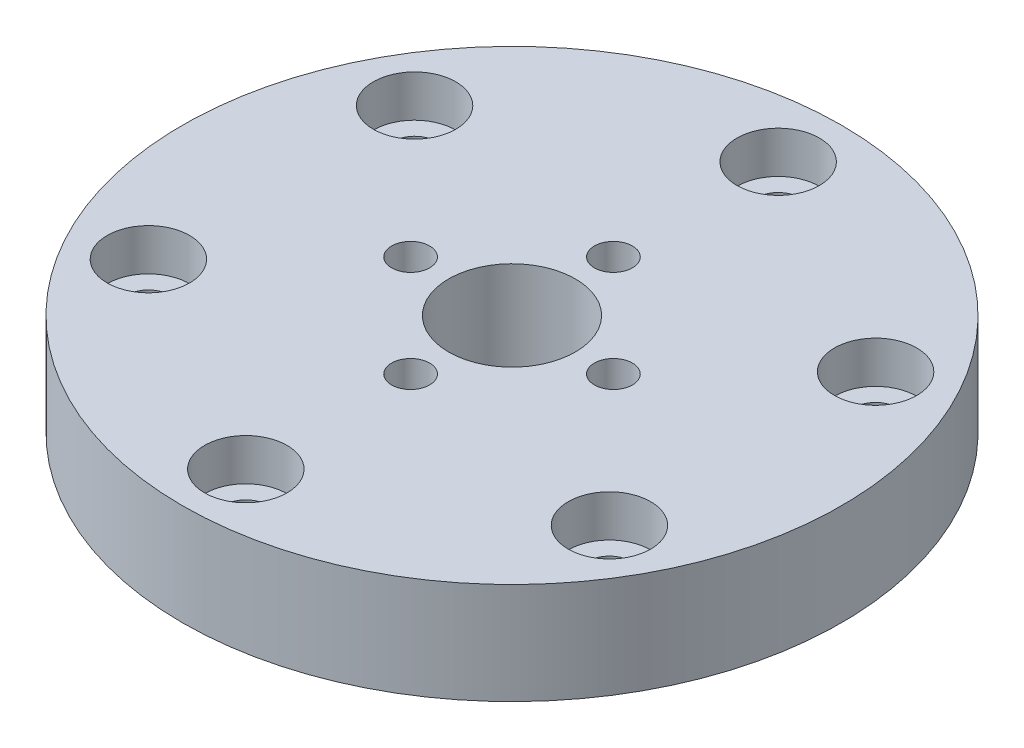
SolidWorks part; units mm, degrees
ref_plane "前视基准面" through (0, 0, 0) normal (0, 0, 1) x (1, 0, 0)
ref_plane "上视基准面" through (0, 0, 0) normal (0, 1, 0) x (1, 0, 0)
ref_plane "右视基准面" through (0, 0, 0) normal (1, 0, 0) x (0, 0, -1)
sketch "草图2" plane through (0, 0, 0) normal (0, 1, 0) x (1, 0, 0)
  circle A0 centre (0, 0) radius 5
  circle A1 centre (0, 0) radius 26
  circle A2 centre (0, 0) radius 8 construction
  circle A3 centre (0, 0) radius 21 construction
  circle A4 centre (0, 8) radius 1.5
  circle A5 centre (8, 0) radius 1.5
  circle A6 centre (0, -8) radius 1.5
  circle A7 centre (-8, 0) radius 1.5
  circle A8 centre (0, 21) radius 1.7
  circle A9 centre (18.1865, 10.5) radius 1.7
  circle A10 centre (18.1865, -10.5) radius 1.7
  circle A11 centre (0, -21) radius 1.7
  circle A12 centre (-18.1865, -10.5) radius 1.7
  circle A13 centre (-18.1865, 10.5) radius 1.7
  point P8 (-18.9922, 12.8987)
  point P9 (0, 0)
  point P17 (0, 0)
  point P30 (0, 0)
  dimension "D1" = 10
  dimension "D2" = 52
  dimension "D3" = 16
  dimension "D4" = 42
  dimension "D5" = 3
  dimension "D7" = 3.4
  dimension "D6" = 4
  dimension "D8" = 6
extrude "凸台-拉伸1" add sketch "草图2" along normal blind 8
sketch "草图3" plane through (0, 8, 0) normal (0, 1, 0) x (1, 0, 0)
  circle A0 centre (0, 21) radius 3.25
  circle A1 centre (18.1865, 10.5) radius 3.25
  circle A2 centre (18.1865, -10.5) radius 3.25
  circle A3 centre (0, -21) radius 3.25
  circle A4 centre (-18.1865, -10.5) radius 3.25
  circle A5 centre (-18.1865, 10.5) radius 3.25
  point P3 (-30.0658, 12.486)
  point P4 (0, 0)
  point P16 (0, 0)
  dimension "D1" = 6.5
  dimension "D2" = 6
extrude "切除-拉伸1" cut sketch "草图3" against normal blind 3.3
